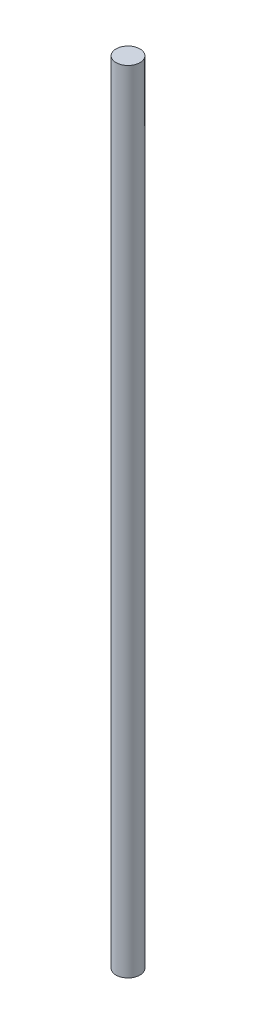
SolidWorks part; units mm, degrees
ref_plane "Front Plane" through (0, 0, 0) normal (0, 0, 1) x (1, 0, 0)
ref_plane "Top Plane" through (0, 0, 0) normal (0, 1, 0) x (1, 0, 0)
ref_plane "Right Plane" through (0, 0, 0) normal (1, 0, 0) x (0, 0, -1)
sketch "Sketch1" plane through (0, 0, 0) normal (0, 1, 0) x (1, 0, 0)
  circle A0 centre (0, 0) radius 5
  dimension "D1" = 10
extrude "Boss-Extrude1" add sketch "Sketch1" along normal blind 331
